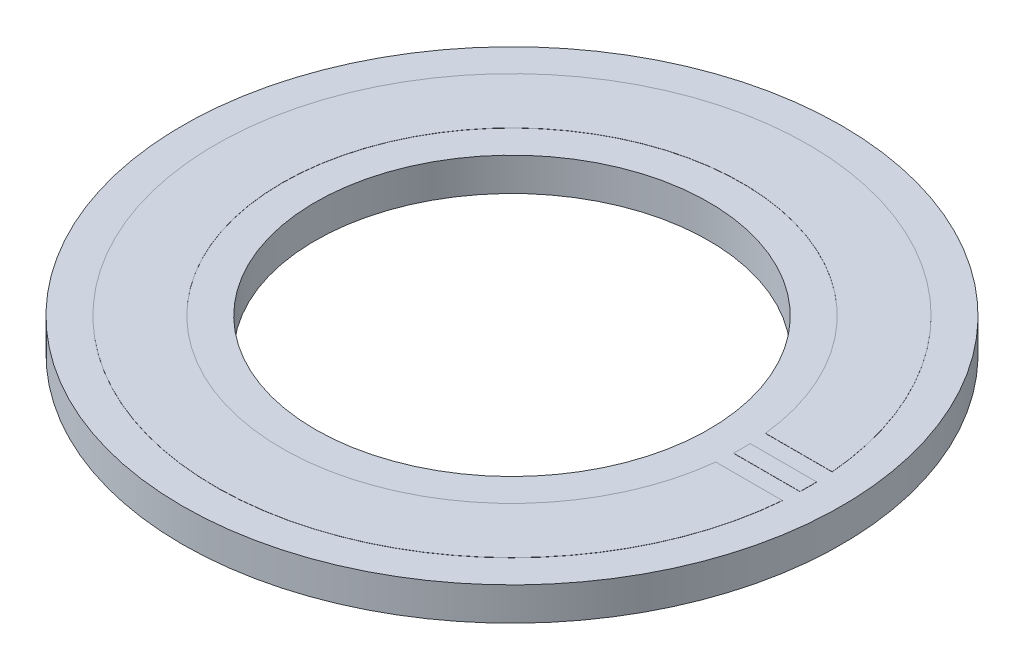
SolidWorks part; units mm, degrees
ref_plane "Спереди" through (0, 0, 0) normal (0, 0, 1) x (1, 0, 0)
ref_plane "Сверху" through (0, 0, 0) normal (0, 1, 0) x (1, 0, 0)
ref_plane "Справа" through (0, 0, 0) normal (1, 0, 0) x (0, 0, -1)
sketch "Эскиз1" plane through (0, 26.1, 0) normal (0, 1, 0) x (1, 0, 0)
  circle A1 centre (0, 0) radius 11.8582
  circle A2 centre (0, 0) radius 19.8582
  circle A65 centre (0, 0) radius 19.8582
  dimension "D1" = 2
extrude "Бобышка-Вытянуть1" add sketch "Эскиз1" along normal blind 2
sketch "Эскиз3" plane through (0, 28.1, 0) normal (0, 1, 0) x (1, 0, 0)
  line L0 (0, 0) -> (0.5, 0) construction
  line L1 (17.8512, -0.5) -> (13.8492, -0.5)
  line L2 (17.7951, -1.5) -> (13.7768, -1.5)
  line L3 (17.8512, 0.5) -> (13.8492, 0.5)
  line L4 (17.7951, 1.5) -> (13.7768, 1.5)
  circle A2 centre (0, 0) radius 17.8582
  arc A3 (17.7951, 1.5) -> (17.7951, -1.5) centre (0, 0) ccw
  arc A4 (17.8512, -0.5) -> (17.8512, 0.5) centre (0, 0) ccw
  circle A5 centre (0, 0) radius 13.8582
  arc A6 (13.8492, -0.5) -> (13.8492, 0.5) centre (0, 0) ccw
  arc A7 (13.7768, 1.5) -> (13.7768, -1.5) centre (0, 0) ccw
  dimension "D3" = 0.5
  dimension "D4" = 1
  dimension "D5" = 1
  dimension "D6" = 1
  dimension "D1" = 2
  dimension "D2" = 2
extrude "Бобышка-Вытянуть3" add sketch "Эскиз3" along normal blind 0.01
